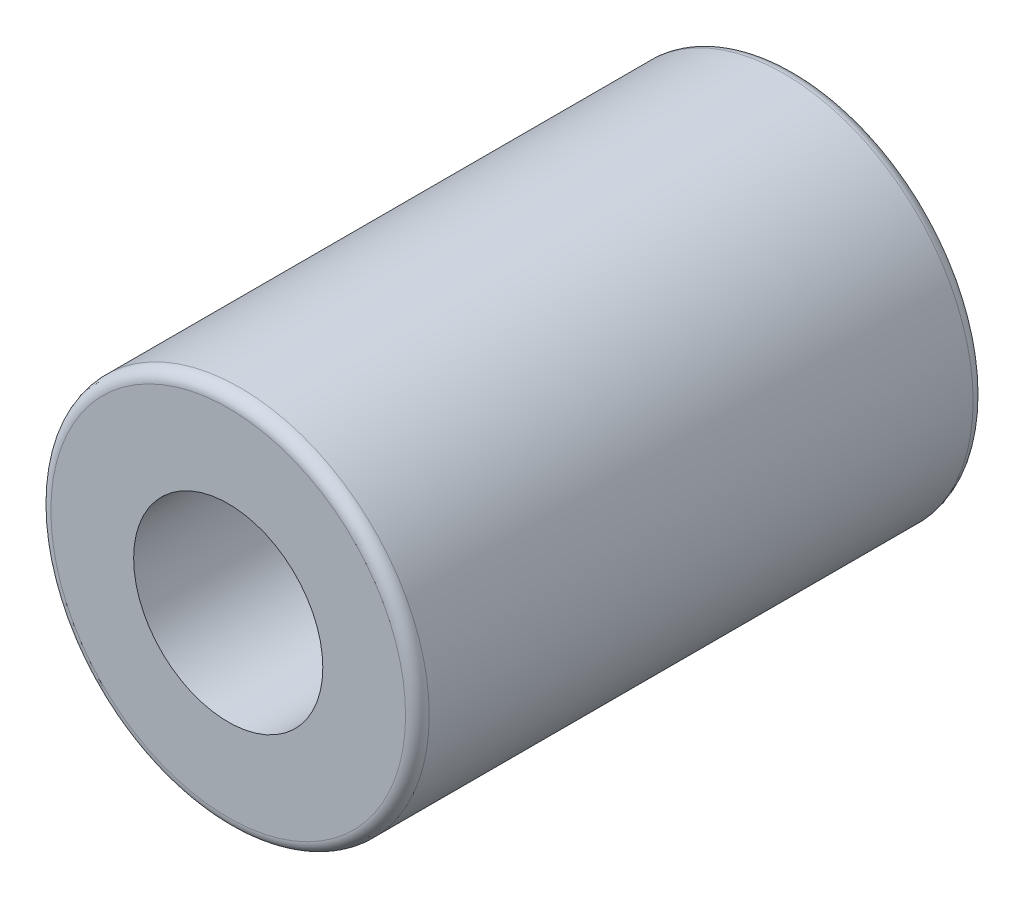
SolidWorks part; units mm, degrees
material "AISI 304"
ref_plane "Front Plane" through (0, 0, 0) normal (0, 0, 1) x (1, 0, 0)
ref_plane "Top Plane" through (0, 0, 0) normal (0, 1, 0) x (1, 0, 0)
ref_plane "Right Plane" through (0, 0, 0) normal (1, 0, 0) x (0, 0, -1)
sketch "Sketch1" plane through (0, 0, 0) normal (0, 0, 1) x (1, 0, 0)
  circle A0 centre (0, 0) radius 4
  circle A1 centre (0, 0) radius 2
  dimension "D1" = 4
  dimension "D2" = 8
extrude "Boss-Extrude1" add sketch "Sketch1" along normal blind 12
fillet "Fillet1" radius 0.25 2 edges at (4, 0, 0) (4, 0, 12)
